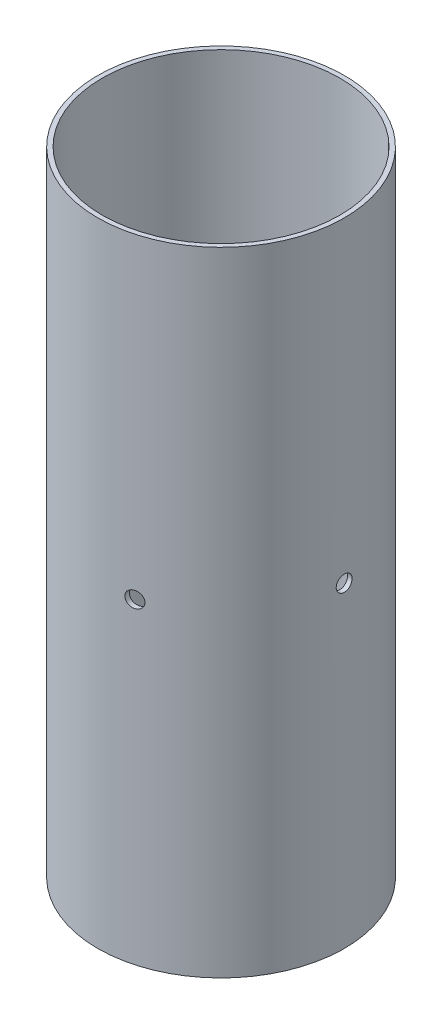
SolidWorks part; units mm, degrees
material "Custom Plastic"
ref_plane "Front Plane" through (0, 0, 0) normal (0, 0, 1) x (1, 0, 0)
ref_plane "Top Plane" through (0, 0, 0) normal (0, 1, 0) x (1, 0, 0)
ref_plane "Right Plane" through (0, 0, 0) normal (1, 0, 0) x (0, 0, -1)
sketch "Sketch1" plane through (0, 0, 0) normal (0, 1, 0) x (1, 0, 0)
  circle A0 centre (0, 0) radius 49.5046
  circle A1 centre (0, 0) radius 47.6885
  dimension "D1" = 99.0092
  dimension "D2" = 95.377
extrude "Boss-Extrude1" add sketch "Sketch1" along normal blind 254 contours A1 | A0
sketch "Sketch2" plane through (0, 0, 0) normal (0, 0, 1) x (1, 0, 0)
  line L0 (-33.5357, 254) -> (-33.5357, 0)
  line L1 (49.5046, 254) -> (-49.5046, 254) construction
  line L2 (-49.5046, 0) -> (49.5046, 0) construction
  line L3 (-33.5357, 127) -> (90.0539, 127) construction
  line L4 (0, 254) -> (0, 0) construction
  circle A0 centre (13.0658, 127) radius 3.175
  dimension "D2" = 6.35
  dimension "D1" = 13.0658
extrude "Cut-Extrude1" cut sketch "Sketch2" against normal through all both and the other way through all contours A0
sketch "Sketch3" plane through (0, 0, 0) normal (1, 0, 0) x (0, 0, -1)
  line L0 (0, 254) -> (0, -12.4194) construction
  line L1 (49.5046, 254) -> (-49.5046, 254) construction
  line L2 (-49.5046, 127) -> (100.1381, 127) construction
  line L3 (-49.5046, 254) -> (-49.5046, 0) construction
  line L4 (49.5046, 0) -> (49.5046, 254) construction
  circle A0 centre (0, 127) radius 3.175
  point P13 (0, 0)
  dimension "D3" = 6.35
  dimension "D1" = 127
  dimension "D2" = 49.5046
extrude "Cut-Extrude2" cut sketch "Sketch3" against normal through all both and the other way through all
